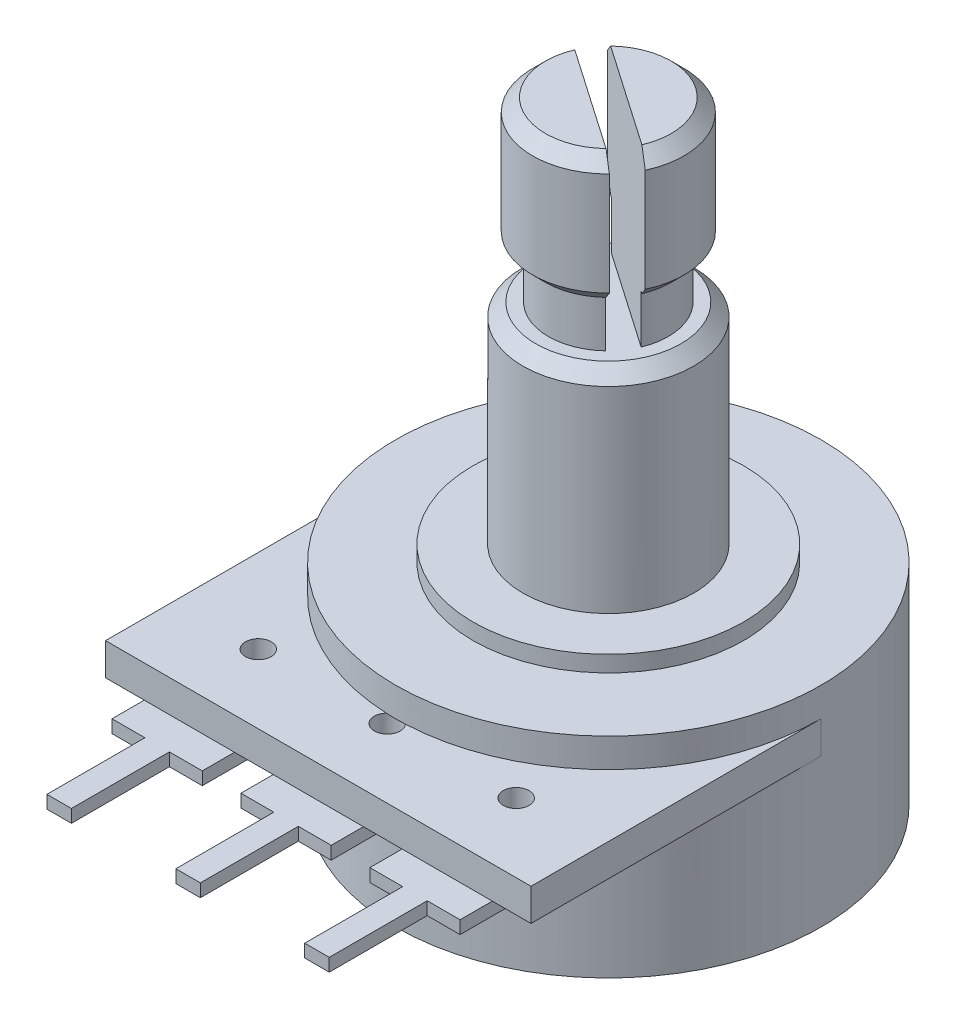
SolidWorks part; units mm, degrees
ref_plane "Front" through (0, 0, 0) normal (0, 0, 1) x (1, 0, 0)
ref_plane "Side" through (0, 0, 0) normal (0, 1, 0) x (1, 0, 0)
ref_plane "Top" through (0, 0, 0) normal (1, 0, 0) x (0, 0, -1)
sketch "Sketch1" plane through (0, 0, 0) normal (0, 0, 1) x (1, 0, 0)
  line L0 (0, 0) -> (8.382, 0)
  line L1 (8.382, 0) -> (8.382, 8.89)
  line L2 (8.382, 8.89) -> (3.3655, 8.89)
  line L3 (3.3655, 8.89) -> (3.3655, 17.145)
  line L4 (3.3655, 17.145) -> (2.3622, 17.145)
  line L5 (2.3622, 17.145) -> (2.3622, 19.05)
  line L6 (2.3622, 19.05) -> (2.9845, 19.05)
  line L7 (2.9845, 19.05) -> (2.9845, 24.13)
  line L8 (2.9845, 24.13) -> (0, 24.13)
  line L9 (0, 24.13) -> (0, 0)
  line L10 (0, 0) -> (0, -13.97) construction
  dimension "D1" = 24.13
  dimension "D2" = 5.08
  dimension "D3" = 15.24
  dimension "D4" = 1.905
  dimension "D5" = 2.9845
  dimension "D6" = 2.3622
  dimension "D7" = 3.3655
  dimension "D8" = 8.382
revolve "Base-Revolve" add sketch "Sketch1" angle 360 about L10
sketch "Sketch2" plane through (0, 0, 0) normal (0, 0, 1) x (1, 0, 0)
  line L0 (-8.382, 7.112) -> (8.382, 7.112)
  line L1 (-8.382, 7.112) -> (-8.382, 5.842)
  line L2 (8.382, 5.842) -> (-8.382, 5.842)
  line L3 (8.382, 5.842) -> (8.382, 7.112)
  line L5 (8.382, 0) -> (8.382, 8.89) construction
  line L6 (-8.382, 8.89) -> (-8.382, 0) construction
  line L7 (-8.382, 0) -> (8.382, 0) construction
  dimension "D1" = 1.27
  dimension "D2" = 5.842
extrude "Boss-Extrude1" add sketch "Sketch2" along normal blind 11.43
sketch "Sketch3" plane through (0, 5.842, 0) normal (0, -1, 0) x (1, 0, 0)
  line L0 (-1.778, 12.7) -> (-0.4826, 12.7)
  line L1 (-1.778, 12.7) -> (-1.778, 8.7122)
  line L3 (1.778, 8.7122) -> (1.778, 12.7)
  line L4 (0.4826, 12.7) -> (1.778, 12.7)
  line L5 (-0.4826, 12.7) -> (-0.4826, 16.5608)
  line L6 (0.4826, 16.5608) -> (-0.4826, 16.5608)
  line L7 (0.4826, 16.5608) -> (0.4826, 12.7)
  line L8 (0, 0) -> (0, 16.5608) construction
  circle A0 centre (0, 0) radius 8.382 construction
  arc A1 (-1.778, 8.7122) -> (1.778, 8.7122) centre (0, 8.7122) ccw
  circle A2 centre (0, 8.7122) radius 0.508
  dimension "D1" = 24.9428
  dimension "D3" = 12.7
  dimension "D5" = 5.7658
  dimension "D6" = 1.016
  dimension "D2" = 0.9652
  dimension "D4" = 3.556
extrude "Boss-Extrude2" add sketch "Sketch3" along normal blind 0.508
sketch "Sketch5" plane through (0, 24.13, 0) normal (0, 1, 0) x (-1, 0, 0)
  circle A0 centre (0, 0) radius 5.334
  circle A1 centre (0, 0) radius 8.382 construction
  circle A2 centre (0, 0) radius 8.382
  dimension "D1" = 10.668
extrude "Cut-Extrude2" cut sketch "Sketch5" against normal blind 15.875
pattern_linear "LPattern1" count 2 spacing 5.08 along (-1, 0, 0) of "Boss-Extrude2"
pattern_linear "LPattern2" count 2 spacing 5.08 along (1, 0, 0) of "Boss-Extrude2"
sketch "Sketch7" plane through (0, 5.842, 0) normal (0, -1, 0) x (1, 0, 0)
  circle A0 centre (-5.08, 8.7122) radius 0.508 construction
  circle A2 centre (5.08, 8.7122) radius 0.508 construction
  circle A3 centre (-5.08, 8.7122) radius 0.508
  circle A4 centre (0, 8.7122) radius 0.508
  circle A5 centre (5.08, 8.7122) radius 0.508
  arc A6 (0.3786, 8.3734) -> (-0.3786, 8.3734) centre (0, 8.7122) ccw construction
extrude "Cut-Extrude3" cut sketch "Sketch7" against normal up to surface (1.27 mm away) up to face at (0, 7.112, 7.8105)
sketch "Sketch8" plane through (0, 24.13, 0) normal (0, 1, 0) x (-1, 0, 0)
  line L0 (-2.7083, 1.254) -> (2.1307, -2.0898)
  line L1 (-2.1307, 2.0898) -> (2.7083, -1.254)
  line L2 (-3.7107, 2.5641) -> (3.7107, -2.5641) construction
  line L3 (0, 0) -> (4.6177, 0) construction
  circle A2 centre (0, 0) radius 2.9845 construction
  arc A3 (-2.1307, 2.0898) -> (-2.7083, 1.254) centre (0, 0) ccw
  arc A4 (2.1307, -2.0898) -> (2.7083, -1.254) centre (0, 0) ccw
  dimension "D1" = 0.508
  dimension "D2" = 1.016
  dimension "D3" = 145.355
extrude "Cut-Extrude4" cut sketch "Sketch8" against normal blind 6.985
chamfer "Chamfer1" distance 0.508 angle 45 5 edges at (1.6966, 24.13, -2.4553) (-1.6966, 24.13, 2.4553) (1.6966, 19.05, -2.4553) (-1.6966, 19.05, 2.4553) (0, 17.145, 3.3655)
